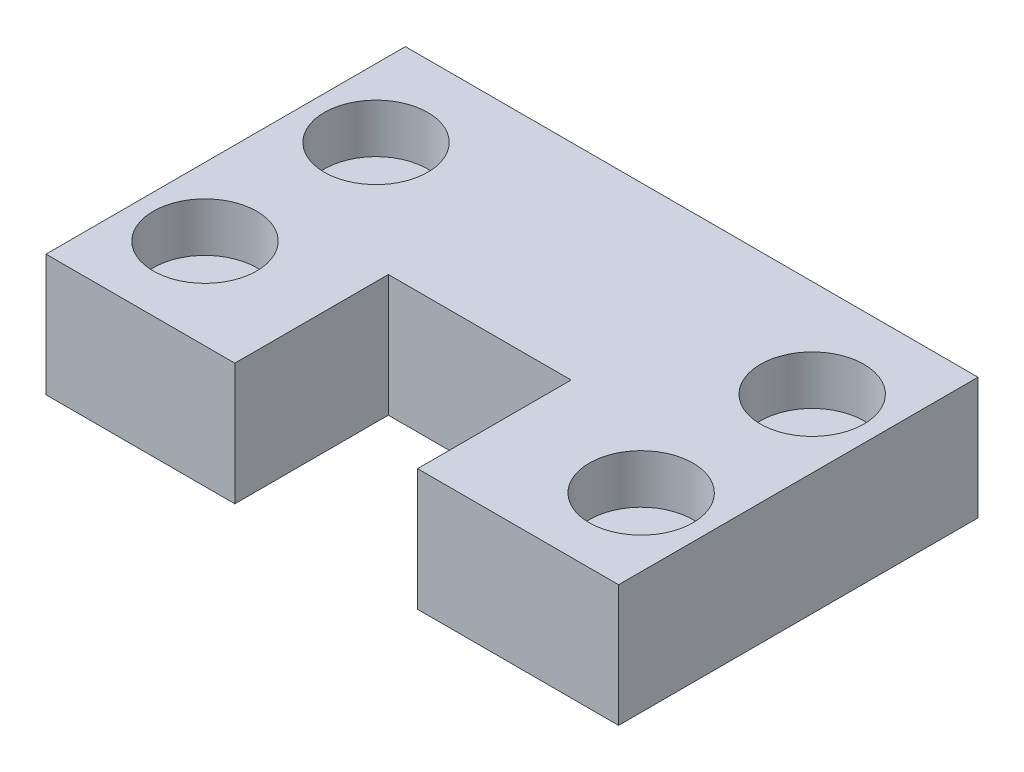
SolidWorks part; units mm, degrees
ref_plane "Front Plane" through (0, 0, 0) normal (0, 0, 1) x (1, 0, 0)
ref_plane "Top Plane" through (0, 0, 0) normal (0, 1, 0) x (1, 0, 0)
ref_plane "Right Plane" through (0, 0, 0) normal (1, 0, 0) x (0, 0, -1)
sketch "Sketch1" plane through (0, 0, 0) normal (0, 1, 0) x (1, 0, 0)
  line L0 (0, 0) -> (0, 29.5)
  line L1 (0, 29.5) -> (47, 29.5)
  line L2 (47, 29.5) -> (47, 0)
  line L3 (47, 0) -> (30.5, 0)
  line L5 (30.5, 12.6) -> (15.5, 12.6)
  line L6 (15.5, 12.6) -> (15.5, 0)
  line L7 (15.5, 0) -> (0, 0)
  line L8 (30.5, 12.6) -> (30.5, 0)
  circle A0 centre (5.58, 7.45) radius 4.25
  circle A1 centre (5.58, 21.55) radius 4.25
  circle A2 centre (41.47, 21.55) radius 4.25
  circle A3 centre (41.47, 7.45) radius 4.25
  point P17 (45.72, 7.45)
  point P18 (41.47, 3.2)
  point P19 (41.47, 17.3)
  point P20 (41.47, 11.7)
  point P21 (41.47, 17.3)
  point P22 (45.72, 21.55)
  point P23 (5.58, 25.8)
  point P24 (5.58, 3.2)
  point P25 (1.33, 21.55)
  dimension "D9" = 8.5
  dimension "D10" = 8.5
  dimension "D11" = 8.5
  dimension "D12" = 8.5
  dimension "D1" = 29.5
  dimension "D2" = 15.5
  dimension "D3" = 15
  dimension "D4" = 16.5
  dimension "D5" = 47
  dimension "D6" = 12.6
  dimension "D7" = 1.28
  dimension "D8" = 3.2
  dimension "D13" = 5.6
  dimension "D14" = 3.7
  dimension "D15" = 3.2
  dimension "D16" = 1.33
extrude "Boss-Extrude2" add sketch "Sketch1" along normal blind 10 contours L6 L7 L0 L1 L2 L3 L8 L5
sketch "Sketch2" plane through (0, 10, 0) normal (0, 1, 0) x (1, 0, 0)
  line L0 (47, 29.5) -> (47, 0) construction
  line L2 (47, 0) -> (30.5, 0) construction
  line L3 (23.5, 29.5) -> (23.5, -8.5891) construction
  line L4 (0, 29.5) -> (47, 29.5) construction
  line L5 (0, 0) -> (0, 29.5) construction
  circle A3 centre (41.4, 7.45) radius 4.25
  circle A4 centre (5.6, 7.45) radius 4.25
  circle A5 centre (5.6, 21.49) radius 4.25
  circle A6 centre (41.4, 21.49) radius 4.25
  point P8 (45.65, 7.45)
  point P11 (41.4, 3.2)
  point P16 (5.6, 25.74)
  point P17 (1.35, 21.49)
  point P22 (5.6, 17.24)
  point P23 (5.6, 11.7)
  dimension "D1" = 3.76
  dimension "D2" = 8.5
  dimension "D3" = 8.5
  dimension "D4" = 1.35
  dimension "D5" = 1.35
  dimension "D6" = 3.2
extrude "Cut-Extrude1" cut sketch "Sketch2" against normal blind 4.02
sketch "Sketch3" plane through (0, 5.98, 0) normal (0, 1, 0) x (1, 0, 0)
  line L0 (23.5, 29.5) -> (23.5, -5.0045) construction
  line L1 (0, 29.5) -> (47, 29.5) construction
  line L2 (0, 14.75) -> (54.6012, 14.75) construction
  line L3 (0, 0) -> (0, 29.5) construction
  circle A0 centre (5.6, 7.45) radius 1.3
  circle A1 centre (41.4, 7.45) radius 1.3
  circle A3 centre (5.6, 21.49) radius 1.3
  circle A4 centre (41.4, 21.49) radius 1.3
  dimension "D1" = 2.6
  dimension "D2" = 2.6
  dimension "D3" = 2.6
  dimension "D4" = 2.6
extrude "Cut-Extrude2" cut sketch "Sketch3" against normal through all
